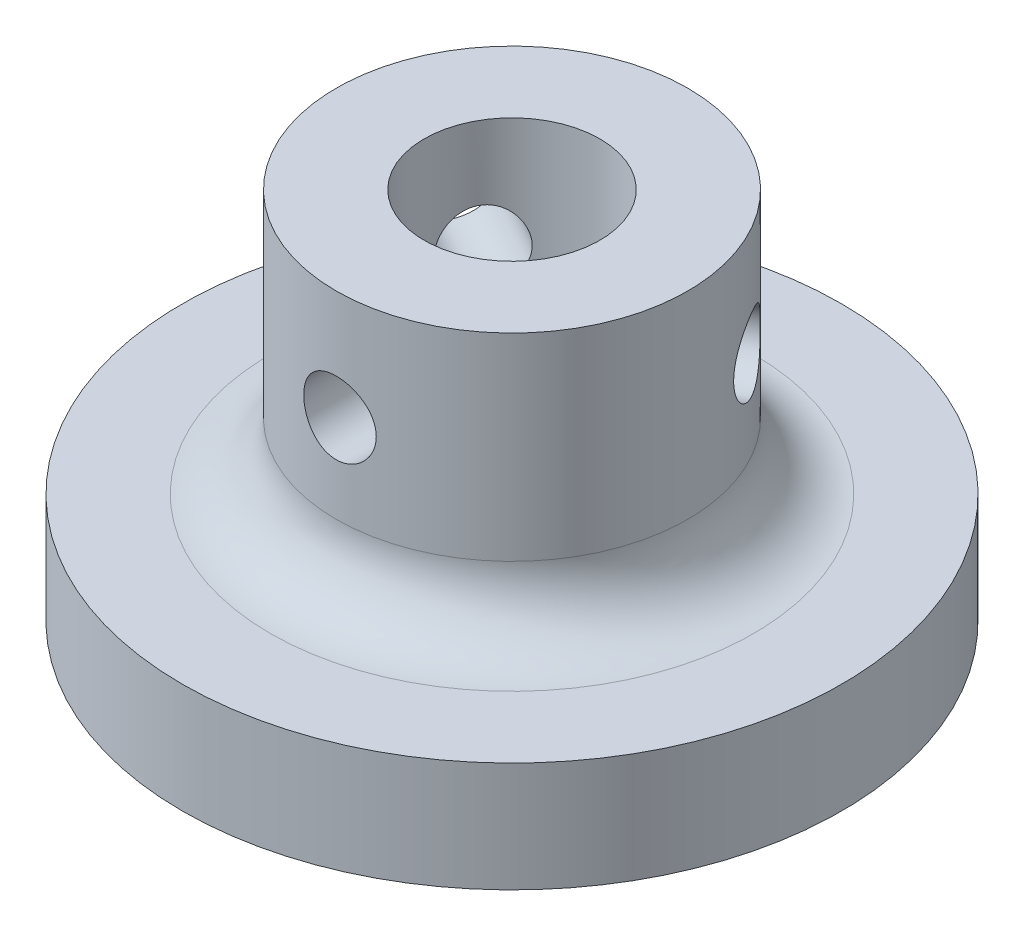
SolidWorks part; units mm, degrees
ref_plane "Front Plane" through (0, 0, 0) normal (0, 0, 1) x (1, 0, 0)
ref_plane "Top Plane" through (0, 0, 0) normal (0, 1, 0) x (1, 0, 0)
ref_plane "Right Plane" through (0, 0, 0) normal (1, 0, 0) x (0, 0, -1)
sketch "Sketch1" plane through (0, 0, 0) normal (0, 0, 1) x (1, 0, 0)
  line L0 (0, 0) -> (0, 15.8) construction
  line L2 (0, 0) -> (15, 0)
  line L3 (15, 0) -> (15, 5)
  line L4 (15, 5) -> (8, 5)
  line L5 (8, 5) -> (8, 17)
  line L6 (8, 17) -> (4, 17)
  line L7 (4, 17) -> (4, 5)
  line L8 (4, 5) -> (0, 5)
  line L9 (0, 5) -> (0, 0)
  dimension "D1" = 8
  dimension "D2" = 30
  dimension "D3" = 5
  dimension "D4" = 17
  dimension "D5" = 4
  dimension "D6" = 12
revolve "Revolve1" add sketch "Sketch1" angle 360 about L0
ref_plane "Plane1" through (0, 0, 8) normal (0, 0, 1) x (1, 0, 0)
fillet "Fillet1" radius 3 1 edges at (0, 5, -8)
hole_wizard "M4 Tapped Hole1" positions "Sketch2" profile "Sketch3" tap size "M4" standard "ISO"
sketch "Sketch2" plane through (0, 0, 8) normal (0, 0, 1) x (1, 0, 0)
  line L0 (8, 17) -> (-8, 17) construction
  point P0 (0, 12)
  point P3 (0, 0)
  dimension "D1" = 5
sketch "Sketch3" plane through (0, 12, 8) normal (1, 0, 0) x (0, -1, 0)
  line L0 (0, 0) -> (0, 16)
  line L1 (0, 16) -> (1.65, 16)
  line L2 (1.65, 16) -> (1.65, 0)
  line L5 (1.65, 0) -> (0, 0)
  line L11 (0, -6.35) -> (0, 107.95) construction
  dimension "Thru Tap Drill Dia." = 3.3
  dimension "Thru Tap Drill Depth" = 16
cosmetic thread "Hole Thread1" parameters "D2"=4
pattern_circular "CirPattern1" count 3 over 360 about axis through (0, 17, 0) along (0, -1, 0) of "M4 Tapped Hole1"
